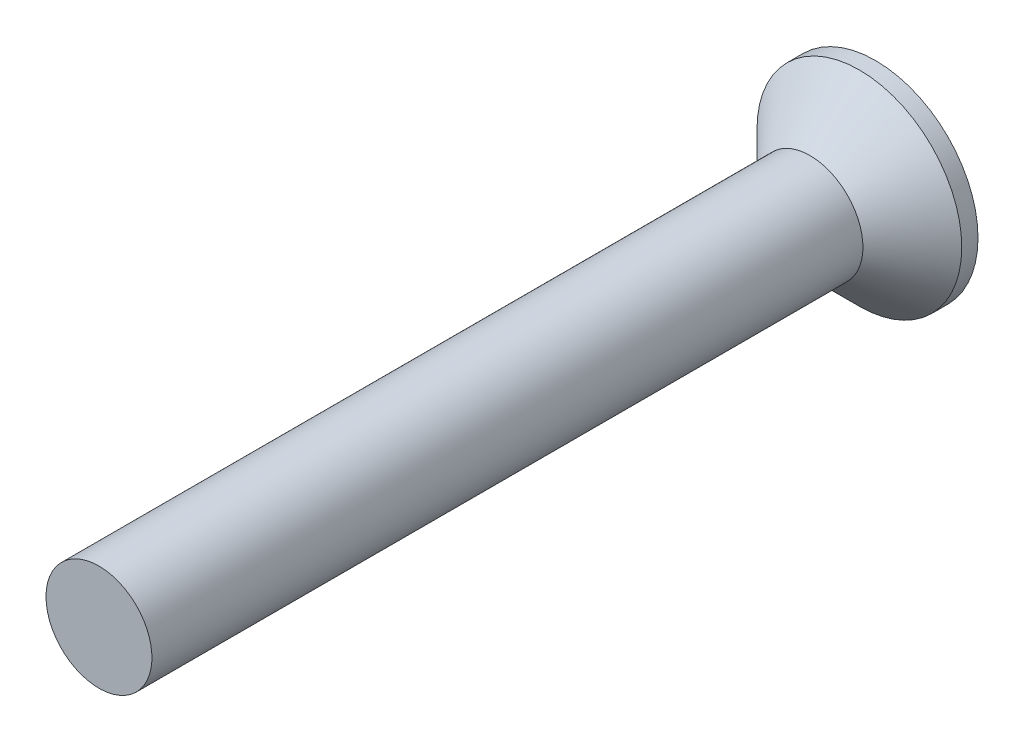
SolidWorks part; units mm, degrees
material "AISI Type 316L stainless steel"
ref_plane "Front Plane" through (0, 0, 0) normal (0, 0, 1) x (1, 0, 0)
ref_plane "Top Plane" through (0, 0, 0) normal (0, 1, 0) x (1, 0, 0)
ref_plane "Right Plane" through (0, 0, 0) normal (1, 0, 0) x (0, 0, -1)
sketch "Sketch1" plane through (0, 0, 0) normal (0, 1, 0) x (1, 0, 0)
  line L0 (0, 0) -> (1.5, 0)
  line L1 (1.5, 0) -> (1.5, 20.14)
  line L3 (2.9, 21.54) -> (2.9, 22)
  line L4 (2.9, 22) -> (0, 22)
  line L5 (0, 22) -> (0, 0)
  line L6 (1.5, 20.14) -> (2.9, 21.54)
  dimension "D1" = 1.5
  dimension "D2" = 2.9
  dimension "D3" = 1.86
  dimension "D4" = 22
  dimension "D5" = 135
revolve "Revolve1" add sketch "Sketch1" angle 360 about L5
sketch "Sketch2" plane through (0, 0, -22) normal (0, 0, -1) x (-1, 0, 0)
  line L0 (0, 0) -> (-0.7217, -1.25) construction
  line L1 (-0.7217, -1.25) -> (0.7217, -1.25)
  line L2 (0.7217, -1.25) -> (0, 0) construction
  line L3 (-1.4434, 0) -> (-0.7217, -1.25)
  line L4 (-0.7217, 1.25) -> (-1.4434, 0)
  line L5 (0.7217, 1.25) -> (-0.7217, 1.25)
  line L6 (1.4434, 0) -> (0.7217, 1.25)
  line L7 (0.7217, -1.25) -> (1.4434, 0)
  point P16 (0, 0)
  dimension "D1" = 1.25
  dimension "D2" = 6
extrude "Cut-Extrude1" cut sketch "Sketch2" against normal blind 2
